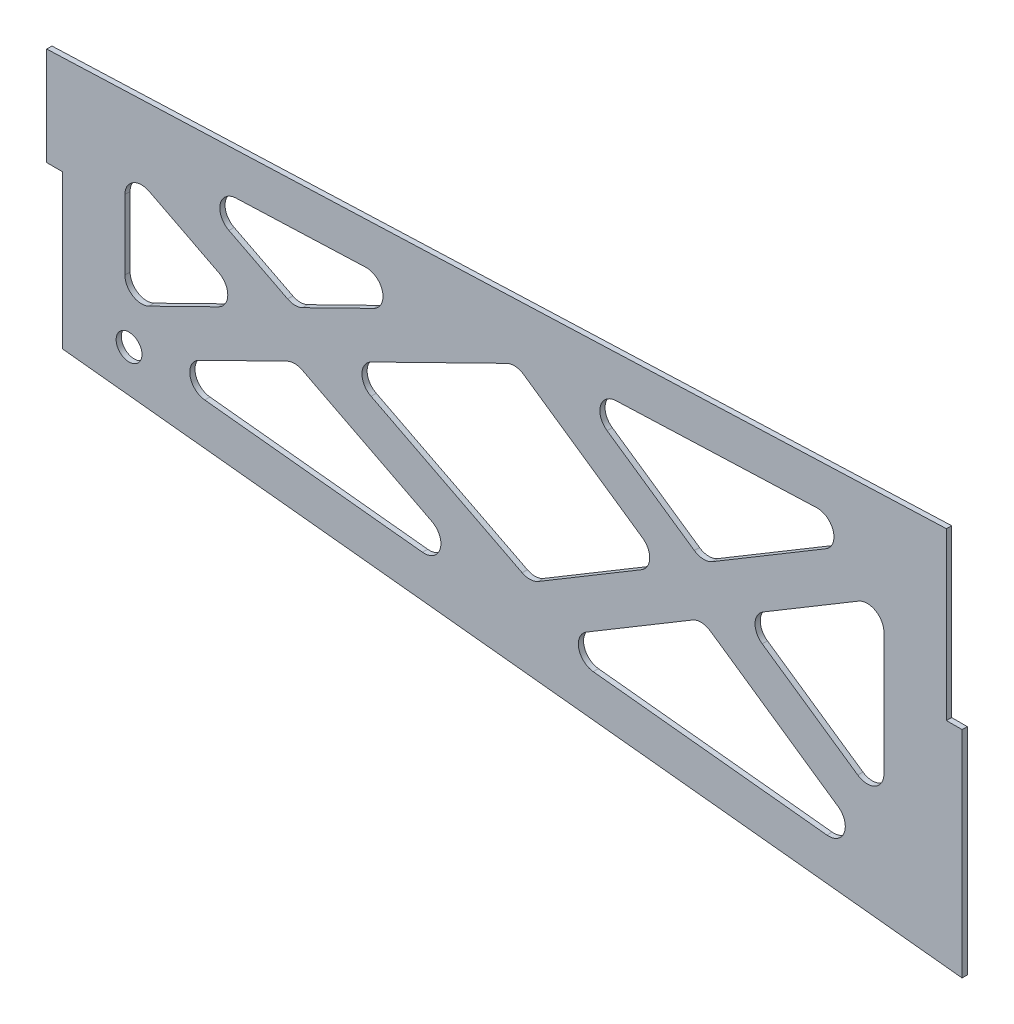
SolidWorks part; units mm, degrees
material "Balsa"
ref_plane "Front Plane" through (0, 0, 0) normal (0, 0, 1) x (1, 0, 0)
ref_plane "Top Plane" through (0, 0, 0) normal (0, 1, 0) x (1, 0, 0)
ref_plane "Right Plane" through (0, 0, 0) normal (1, 0, 0) x (0, 0, -1)
sketch "Sketch1" plane through (0, 0, 0) normal (0, 0, 1) x (1, 0, 0)
  line L1 (-274.0653, 28.9491) -> (0, 0)
  line L3 (0, 116.332) -> (0, 0)
  line L4 (0, 116.332) -> (-278.8278, 105.6571)
  line L7 (-278.8278, 88.3851) -> (-278.8278, 75.6851)
  line L8 (-278.8278, 105.6571) -> (-278.8278, 88.3851)
  line L9 (-278.8278, 75.6851) -> (-274.0653, 75.6851)
  line L10 (-274.0653, 75.6851) -> (-274.0653, 28.9491)
  dimension "D1" = 275.59
  dimension "D2" = 116.332
  dimension "D3" = 29.972
  dimension "D5" = 46.736
  dimension "D6" = 279.0321
  dimension "D7" = 4.7625
extrude "Boss-Extrude1" add sketch "Sketch1" along normal blind 1.5875
sketch "Sketch2" plane through (0, 0, 1.5875) normal (0, 0, 1) x (1, 0, 0)
  line L0 (0, 116.332) -> (0, 65.532)
  line L1 (0, 0) -> (0, 116.332) construction
  line L4 (0, 116.332) -> (-278.8278, 105.6571) construction
  line L5 (-4.7625, 116.1497) -> (0, 116.332)
  line L6 (0, -5.47) -> (-4.7625, -5.47)
  line L7 (-4.7625, -5.47) -> (-4.7625, 0.5031)
  line L8 (-274.0653, 28.9491) -> (0, 0) construction
  line L9 (-4.7625, 0.5031) -> (0, 0)
  line L10 (0, 0) -> (0, -5.47)
  line L11 (0, 65.532) -> (-4.7625, 65.532)
  line L12 (-4.7625, 65.532) -> (-4.7625, 116.1497)
  dimension "D1" = 50.8
  dimension "D2" = 71.002
  dimension "D3" = 4.7625
  dimension "D4" = 4.7625
extrude "Cut-Extrude1" cut sketch "Sketch2" against normal through all
sketch "Sketch3" plane through (0, 0, 1.5875) normal (0, 0, 1) x (1, 0, 0)
  line L0 (-240.6578, 94.4091) -> (-157.7552, 97.583)
  line L1 (-4.7625, 116.1497) -> (-278.8278, 105.6571) construction
  line L2 (-274.0653, 75.6851) -> (-274.0653, 28.9491) construction
  line L3 (-157.7552, 97.583) -> (-203.1859, 75.2612)
  line L4 (-203.1859, 75.2612) -> (-240.6578, 94.4091)
  line L5 (-255.0153, 87.4837) -> (-255.0153, 49.7953)
  line L6 (-255.0153, 49.7953) -> (-217.4147, 68.27)
  line L7 (-217.4147, 68.27) -> (-255.0153, 87.4837)
  line L8 (-248.2103, 38.9887) -> (-203.2975, 61.0562)
  line L9 (-203.2975, 61.0562) -> (-137.1561, 27.2582)
  line L10 (-137.1561, 27.2582) -> (-248.2103, 38.9887)
  line L11 (-189.0687, 68.0473) -> (-136.0057, 94.1193)
  line L12 (-136.0057, 94.1193) -> (-90.8367, 62.9629)
  line L13 (-90.8367, 62.9629) -> (-131.4961, 38.628)
  line L14 (-131.4961, 38.628) -> (-189.0687, 68.0473)
  line L16 (-120.7161, 99.0011) -> (-24.4662, 102.686)
  line L17 (-24.4662, 102.686) -> (-78.8609, 70.1305)
  line L18 (-78.8609, 70.1305) -> (-120.7161, 99.0011)
  line L19 (-127.4725, 26.2354) -> (-79.3478, 55.0382)
  line L20 (-79.3478, 55.0382) -> (-21.3379, 15.0245)
  line L21 (-21.3379, 15.0245) -> (-127.4725, 26.2354)
  line L22 (-67.372, 62.2058) -> (-23.8125, 88.2764)
  line L23 (-23.8125, 88.2764) -> (-23.8125, 32.1596)
  line L24 (-23.8125, 32.1596) -> (-67.372, 62.2058)
  line L25 (-274.0653, 28.9491) -> (0, 0) construction
  line L26 (-4.7625, 116.1497) -> (-4.7625, 65.532) construction
  dimension "D1" = 12.7
  dimension "D2" = 12.7
  dimension "D3" = 12.7
  dimension "D4" = 12.7
  dimension "D5" = 12.7
  dimension "D6" = 12.7
  dimension "D7" = 12.7
  dimension "D8" = 12.7
  dimension "D9" = 19.05
  dimension "D10" = 19.05
  dimension "D11" = 12.7
  dimension "D12" = 12.7
  dimension "D13" = 45.4307
  dimension "D14" = 74.2763
  dimension "D15" = 48.1246
  dimension "D16" = 58.0099
  dimension "D17" = 54.3947
  dimension "D18" = 41.8552
  dimension "D19" = 37.4719
  dimension "D20" = 53.063
extrude "Cut-Extrude2" cut sketch "Sketch3" against normal up to surface (1.5875 mm away) contours L5 L6 L7 | L4 L0 L3 | L14 L11 L12 L13 | L10 L8 L9 | L21 L19 L20 | L16 L17 L18 | L24 L22 L23 up to face at (-139.4139, 66.6488, 0)
fillet "Fillet1" radius 5.08 22 edges at (-203.2975, 61.0562, 0.7937) (-255.0153, 87.4837, 0.7937) (-255.0153, 49.7953, 0.7937) (-248.2103, 38.9887, 0.7937) (-127.4725, 26.2354, 0.7937) (-136.0057, 94.1193, 0.7937) (-24.4662, 102.686, 0.7937) (-79.3478, 55.0382, 0.7937) (-23.8125, 88.2764, 0.7937) (-217.4147, 68.27, 0.7937) (-137.1561, 27.2582, 0.7937) (-90.8367, 62.9629, 0.7937) (-21.3379, 15.0245, 0.7937) (-23.8125, 32.1596, 0.7937) (-78.8609, 70.1305, 0.7937) (-131.4961, 38.628, 0.7937) (-120.7161, 99.0011, 0.7937) (-189.0687, 68.0473, 0.7937) (-67.372, 62.2058, 0.7937) (-240.6578, 94.4091, 0.7937) (-157.7552, 97.583, 0.7937) (-203.1859, 75.2612, 0.7937)
sketch "Sketch4" plane through (0, 0, 1.5875) normal (0, 0, 1) x (1, 0, 0)
  line L0 (-274.0653, 28.9491) -> (0, 0) construction
  line L1 (-274.0653, 75.6851) -> (-274.0653, 28.9491) construction
  circle A0 centre (-253.7453, 39.5734) radius 3.937
  dimension "D1" = 7.874
  dimension "D2" = 12.7
  dimension "D3" = 20.32
extrude "Cut-Extrude3" cut sketch "Sketch4" against normal through all
